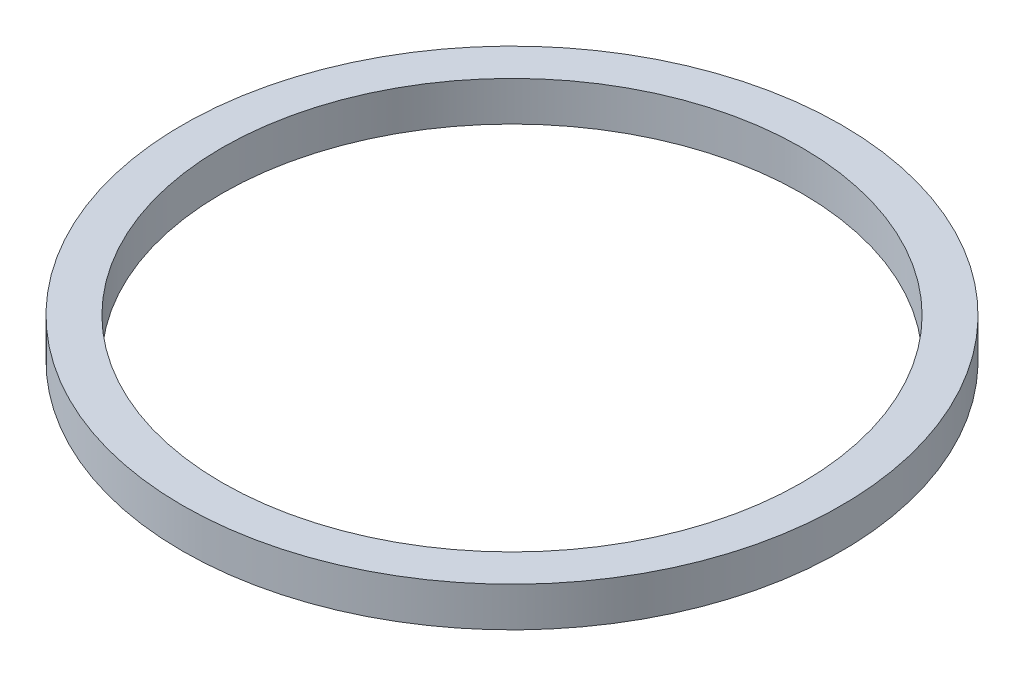
SolidWorks part; units mm, degrees
ref_plane "Alzado" through (0, 0, 0) normal (0, 0, 1) x (1, 0, 0)
ref_plane "Planta" through (0, 0, 0) normal (0, 1, 0) x (1, 0, 0)
ref_plane "Vista lateral" through (0, 0, 0) normal (1, 0, 0) x (0, 0, -1)
sketch "Croquis1" plane through (0, 0, 0) normal (0, 1, 0) x (1, 0, 0)
  circle A0 centre (0, 0) radius 25
  circle A1 centre (0, 0) radius 22
  dimension "D1" = 50
  dimension "D2" = 3
extrude "Saliente-Extruir1" add sketch "Croquis1" along normal blind 3
